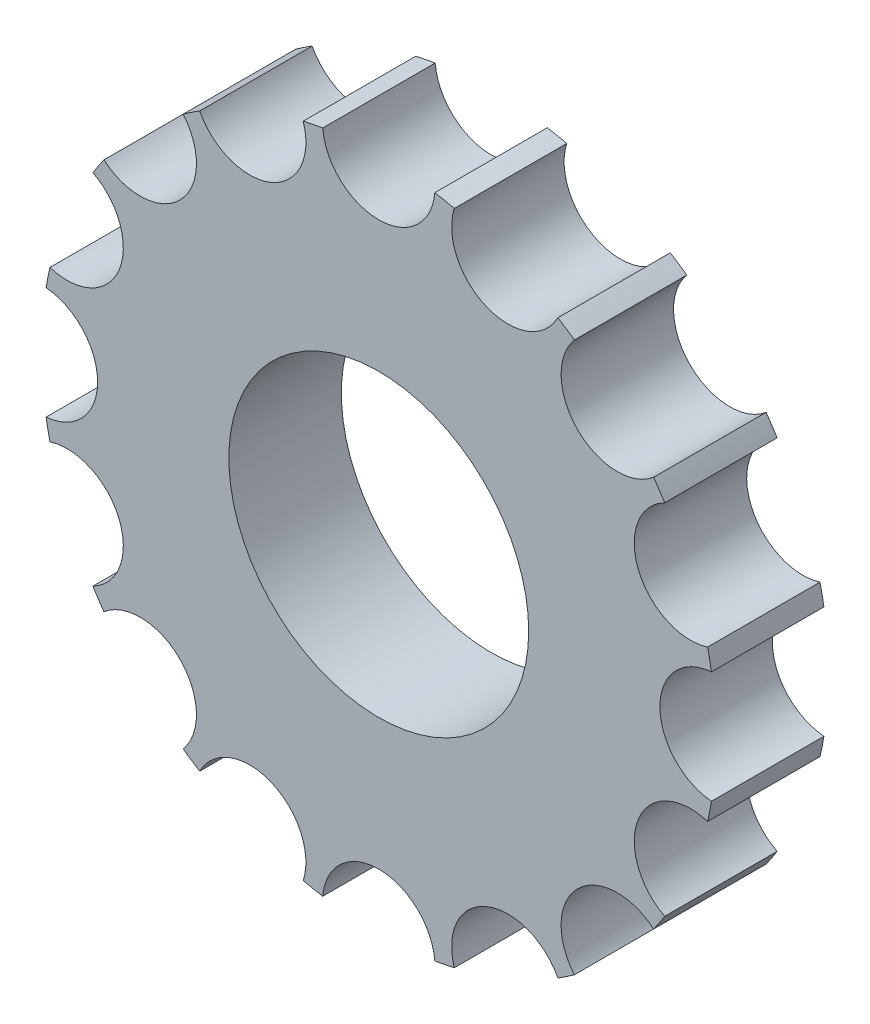
SolidWorks part; units mm, degrees
ref_plane "Front Plane" through (0, 0, 0) normal (0, 0, 1) x (1, 0, 0)
ref_plane "Top Plane" through (0, 0, 0) normal (0, 1, 0) x (1, 0, 0)
ref_plane "Right Plane" through (0, 0, 0) normal (1, 0, 0) x (0, 0, -1)
sketch "Sketch1" plane through (0, 0, 0) normal (0, 0, 1) x (1, 0, 0)
  circle A0 centre (0, 0) radius 45
  circle A1 centre (0, 0) radius 20
  dimension "D1" = 90
  dimension "D2" = 40
extrude "Boss-Extrude1" add sketch "Sketch1" along normal blind 15
sketch "Sketch2" plane through (0, 0, 15) normal (0, 0, 1) x (1, 0, 0)
  circle A0 centre (0, 45) radius 7.5
  circle A1 centre (0, 0) radius 45 construction
  circle A2 centre (17.2208, 41.5746) radius 7.5
  circle A3 centre (31.8198, 31.8198) radius 7.5
  circle A4 centre (41.5746, 17.2208) radius 7.5
  circle A5 centre (45, 0) radius 7.5
  circle A6 centre (41.5746, -17.2208) radius 7.5
  circle A7 centre (31.8198, -31.8198) radius 7.5
  circle A8 centre (17.2208, -41.5746) radius 7.5
  circle A9 centre (0, -45) radius 7.5
  circle A10 centre (-17.2208, -41.5746) radius 7.5
  circle A11 centre (-31.8198, -31.8198) radius 7.5
  circle A12 centre (-41.5746, -17.2208) radius 7.5
  circle A13 centre (-45, 0) radius 7.5
  circle A14 centre (-41.5746, 17.2208) radius 7.5
  circle A15 centre (-31.8198, 31.8198) radius 7.5
  circle A16 centre (-17.2208, 41.5746) radius 7.5
  point P37 (0, 0)
  dimension "D1" = 15
  dimension "D2" = 16
extrude "Cut-Extrude1" cut sketch "Sketch2" against normal blind 15
